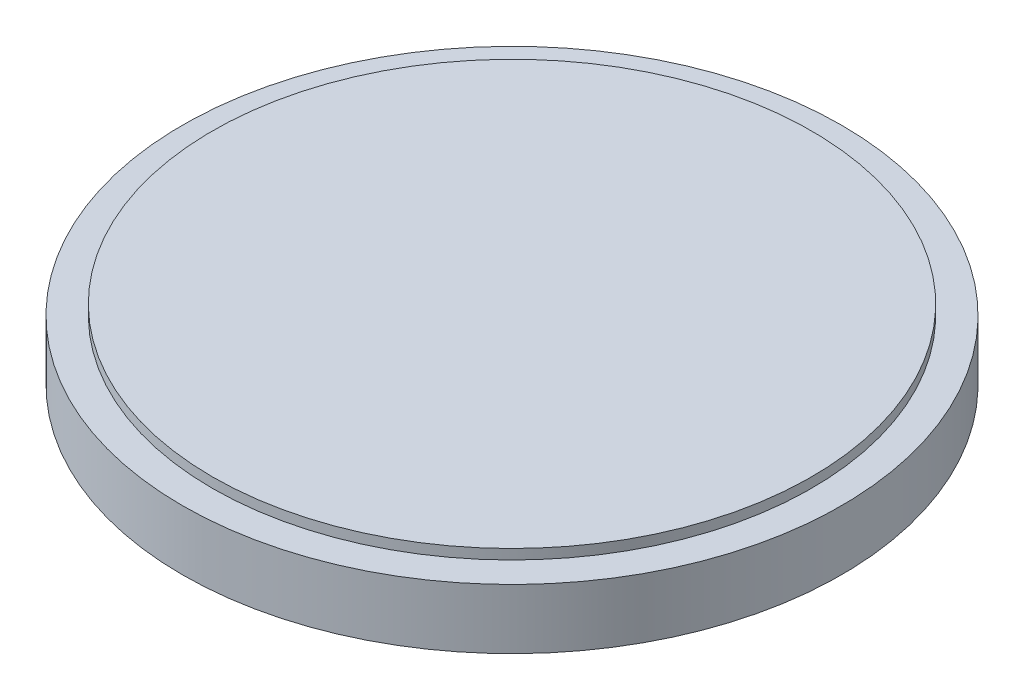
SolidWorks part; units mm, degrees
material "6061 Alloy"
ref_plane "Front Plane" through (0, 0, 0) normal (0, 0, 1) x (1, 0, 0)
ref_plane "Top Plane" through (0, 0, 0) normal (0, 1, 0) x (1, 0, 0)
ref_plane "Right Plane" through (0, 0, 0) normal (1, 0, 0) x (0, 0, -1)
sketch "Sketch1" plane through (0, 0, 0) normal (0, 1, 0) x (1, 0, 0)
  circle A0 centre (0, 0) radius 33
  circle A1 centre (0, 0) radius 29
  dimension "D1" = 58
  dimension "D2" = 66
extrude "BEZEL_RING" add sketch "Sketch1" along normal blind 6
sketch "Sketch2" plane through (0, 0, 0) normal (0, 1, 0) x (1, 0, 0)
  circle A0 centre (0, 0) radius 30
  circle A2 centre (0, 0) radius 33 construction
  dimension "D1" = 60
extrude "Cut-Extrude1" cut sketch "Sketch2" along normal blind 1
sketch "Sketch4" plane through (0, 6, 0) normal (0, 1, 0) x (1, 0, 0)
  circle A0 centre (0, 0) radius 30
  dimension "D1" = 60
extrude "Boss-Extrude2" add sketch "Sketch4" along normal blind 1 separate body
